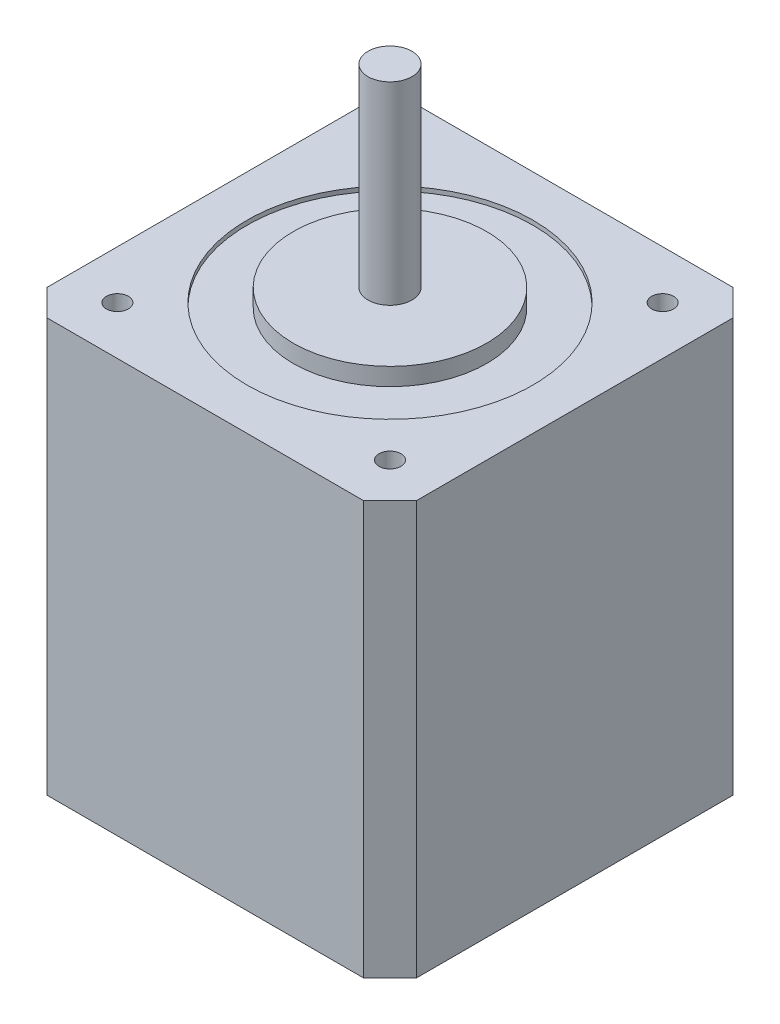
SolidWorks part; units mm, degrees
ref_plane "前基準面" through (0, 0, 0) normal (0, 0, 1) x (1, 0, 0)
ref_plane "上基準面" through (0, 0, 0) normal (0, 1, 0) x (1, 0, 0)
ref_plane "右基準面" through (0, 0, 0) normal (1, 0, 0) x (0, 0, -1)
sketch "草圖1" plane through (0, 0, 0) normal (0, 1, 0) x (1, 0, 0)
  line L1 (-21, -21) -> (21, -21)
  line L2 (-21, -21) -> (-21, 21)
  line L3 (-21, 21) -> (21, 21)
  line L4 (21, -21) -> (21, 21)
  line L5 (-21, -21) -> (21, 21) construction
  line L6 (-21, 21) -> (21, -21) construction
  point P0 (0, 0)
  dimension "D1" = 42
  dimension "D2" = 42
extrude "填料-伸長1" add sketch "草圖1" along normal blind 47
sketch "草圖2" plane through (0, 47, 0) normal (0, 1, 0) x (1, 0, 0)
  circle A0 centre (0, 0) radius 16.25
  dimension "D1" = 32.5
extrude "除料-伸長1" cut sketch "草圖2" against normal blind 0.5
sketch "草圖3" plane through (0, 46.5, 0) normal (0, 1, 0) x (1, 0, 0)
  circle A0 centre (0, 0) radius 11
  dimension "D1" = 22
extrude "填料-伸長2" add sketch "草圖3" along normal blind 2
sketch "草圖4" plane through (0, 48.5, 0) normal (0, 1, 0) x (1, 0, 0)
  circle A0 centre (0, 0) radius 2.5
  dimension "D1" = 5
extrude "填料-伸長3" add sketch "草圖4" along normal blind 22
chamfer "導角1" distance 3 angle 45 4 edges at (-21, 23.5, 21) (21, 23.5, 21) (-21, 23.5, -21) (21, 23.5, -21)
hole_wizard "M3 螺紋孔1" positions "草圖5" profile "草圖6" tap size "M3" standard "ISO"
sketch "草圖5" plane through (0, 47, 0) normal (0, 1, 0) x (1, 0, 0)
  point P0 (-15.5, 15.5)
  point P2 (-15.5, -15.5)
  point P4 (15.5, 15.5)
  point P6 (15.5, -15.5)
  dimension "D1" = 15.5
  dimension "D2" = 15.5
  dimension "D3" = 31
  dimension "D4" = 31
sketch "草圖6" plane through (-15.5, 47, -15.5) normal (1, 0, 0) x (0, 0, 1)
  line L0 (0, 0) -> (0, 8.2511)
  line L1 (0, 8.2511) -> (1.25, 7.5)
  line L2 (1.25, 7.5) -> (1.25, 0)
  line L5 (1.25, 0) -> (0, 0)
  line L10 (0, 8.2511) -> (-1.25, 7.5) construction
  line L11 (0, -6.35) -> (0, 107.95) construction
  dimension "螺孔鑽直徑" = 2.5
  dimension "螺孔鑽深度" = 7.5
  dimension "導頭角度" = 118
cosmetic thread "鑽孔螺紋1" parameters "D1"=6, "D2"=3
cosmetic thread "鑽孔螺紋2" parameters "D1"=6, "D2"=3
cosmetic thread "鑽孔螺紋3" parameters "D1"=6, "D2"=3
cosmetic thread "鑽孔螺紋4" parameters "D1"=6, "D2"=3
